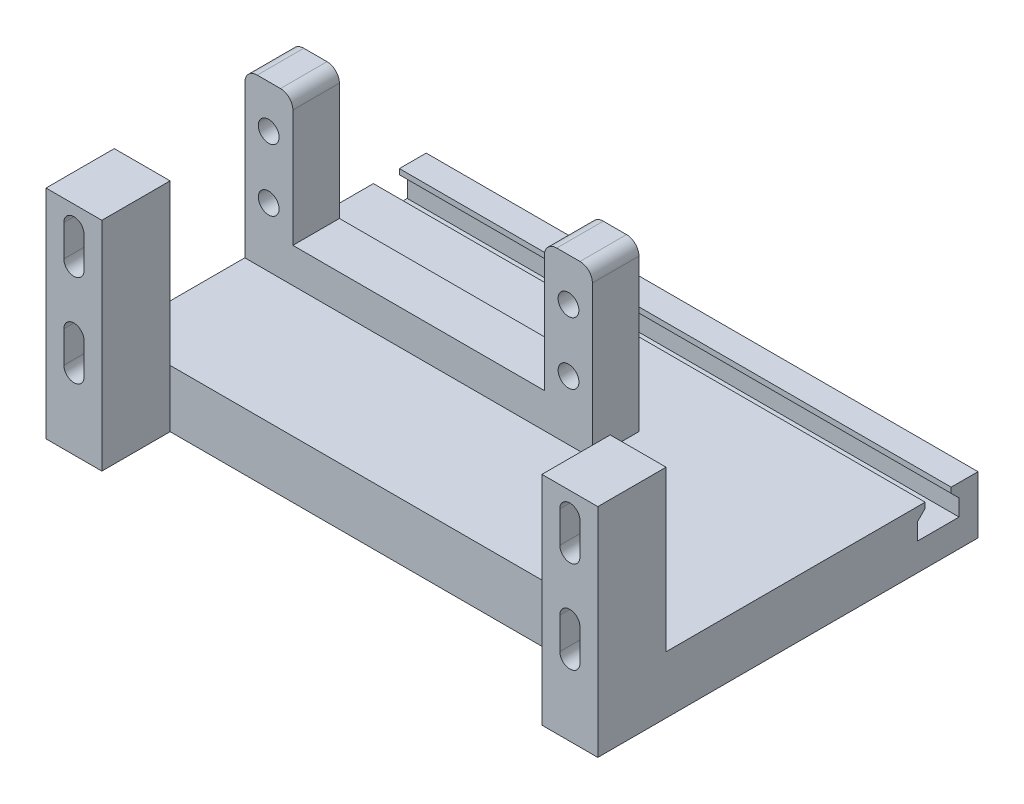
SolidWorks part; units mm, degrees
ref_plane "Front Plane" through (0, 0, 0) normal (0, 0, 1) x (1, 0, 0)
ref_plane "Top Plane" through (0, 0, 0) normal (0, 1, 0) x (1, 0, 0)
ref_plane "Right Plane" through (0, 0, 0) normal (1, 0, 0) x (0, 0, -1)
sketch "Sketch1" plane through (0, 0, 0) normal (0, 1, 0) x (1, 0, 0)
  line L1 (-44.45, -19.625) -> (44.45, -19.625)
  line L2 (-44.45, -19.625) -> (-44.45, 19.625)
  line L3 (-44.45, 19.625) -> (44.45, 19.625)
  line L4 (44.45, -19.625) -> (44.45, 19.625)
  line L5 (-44.45, -19.625) -> (44.45, 19.625) construction
  line L6 (-44.45, 19.625) -> (44.45, -19.625) construction
  point P0 (0, 0)
  dimension "D1" = 88.9
  dimension "D2" = 39.25
extrude "Boss-Extrude1" add sketch "Sketch1" along normal blind 9.25
sketch "Sketch2" plane through (0, 9.25, 0) normal (0, 1, 0) x (1, 0, 0)
  line L0 (0, 19.625) -> (0, -1.985) construction
  line L2 (-44.45, 19.625) -> (-44.45, -19.625) construction
  line L3 (-44.45, -9.5982) -> (11.55, -9.5982)
  line L4 (-44.45, -9.5982) -> (-44.45, -2.0982)
  line L5 (-44.45, -2.0982) -> (11.55, -2.0982)
  line L6 (11.55, -9.5982) -> (11.55, -2.0982)
  line L7 (-44.45, -9.5982) -> (11.55, -2.0982) construction
  line L8 (-44.45, -2.0982) -> (11.55, -9.5982) construction
  line L9 (44.45, 19.625) -> (-44.45, 19.625) construction
  point P9 (-16.45, -5.8482)
  dimension "D1" = 56
  dimension "D2" = 7.5
  dimension "D3" = 21.61
extrude "Boss-Extrude2" add sketch "Sketch2" along normal blind 26.49
sketch "Sketch3" plane through (0, 0, 9.5982) normal (0, 0, 1) x (1, 0, 0)
  line L0 (-16.45, 9.25) -> (-16.45, 14.86) construction
  line L1 (-44.45, 9.25) -> (11.55, 9.25) construction
  line L2 (-36.705, 14.86) -> (3.805, 14.86)
  line L3 (3.805, 14.86) -> (3.805, 35.74)
  line L4 (-44.45, 35.74) -> (11.55, 35.74) construction
  line L5 (3.805, 35.74) -> (-36.705, 35.74)
  line L6 (-36.705, 35.74) -> (-36.705, 14.86)
  point P7 (-16.45, 14.86)
extrude "Cut-Extrude2" cut sketch "Sketch3" against normal blind 8.49
sketch "Sketch5" plane through (0, 0, 9.5982) normal (0, 0, 1) x (1, 0, 0)
  line L0 (-16.45, 9.25) -> (-16.45, 18.82) construction
  line L1 (-44.45, 9.25) -> (11.55, 9.25) construction
  line L2 (-40.6, 18.82) -> (7.7, 18.82) construction
  line L3 (-40.6, 18.82) -> (-40.6, 28.82) construction
  circle A0 centre (-40.6, 18.82) radius 1.675
  circle A1 centre (-40.6, 28.82) radius 1.675
  circle A2 centre (7.7, 18.82) radius 1.675
  circle A3 centre (7.7, 28.82) radius 1.675
  point P7 (-16.45, 18.82)
  dimension "D1" = 3.35
  dimension "D2" = 3.35
extrude "Cut-Extrude3" cut sketch "Sketch5" against normal blind 8.49
sketch "Sketch10" plane through (-44.45, 0, 0) normal (-1, 0, 0) x (0, 0, 1)
  line L0 (-19.625, 9.25) -> (-19.625, 4.4433) construction
  line L1 (-19.625, 9.25) -> (-19.625, 0) construction
  line L2 (-19.625, 4.4433) -> (-16.575, 4.4433) construction
  line L3 (-16.575, 4.4433) -> (-9.845, 4.4433)
  line L4 (-16.575, 4.4433) -> (-16.575, 7.1133)
  line L5 (-9.845, 4.4433) -> (-9.845, 7.1133)
  line L6 (-19.625, 9.25) -> (-15.305, 9.25) construction
  line L7 (-19.625, 9.25) -> (2.0982, 9.25) construction
  line L8 (-15.305, 9.25) -> (-11.115, 9.25)
  line L9 (-11.1178, 8.3861) -> (-11.115, 9.25)
  line L10 (-11.1178, 8.3861) -> (-9.845, 7.1133)
  line L11 (-16.575, 7.1133) -> (-15.3022, 8.3861)
  line L12 (-15.3022, 8.3861) -> (-15.305, 9.25)
extrude "Cut-Extrude4" cut sketch "Sketch10" against normal blind 91.49
fillet "Fillet1" radius 2 2 edges at (-36.705, 35.74, 5.8482) (-44.45, 35.74, 5.8482)
fillet "Fillet2" radius 2 2 edges at (11.55, 35.74, 5.8482) (3.805, 35.74, 5.8482)
sketch "Sketch12" plane through (0, 0, 19.625) normal (0, 0, 1) x (1, 0, 0)
  line L1 (-44.45, 0) -> (44.45, 0)
  line L2 (-44.45, 0) -> (-44.45, 9.25)
  line L3 (-44.45, 9.25) -> (44.45, 9.25)
  line L4 (44.45, 0) -> (44.45, 9.25)
  line L5 (-44.45, 0) -> (44.45, 9.25) construction
  line L6 (-44.45, 9.25) -> (44.45, 0) construction
  point P4 (0, 4.625)
extrude "Boss-Extrude3" add sketch "Sketch12" along normal blind 11
sketch "Sketch16" plane through (0, 0, 0) normal (0, 1, 0) x (1, 0, 0)
  line L1 (44.45, -30.625) -> (35.45, -30.625)
  line L2 (44.45, -30.625) -> (44.45, -41.625)
  line L3 (44.45, -41.625) -> (35.45, -41.625)
  line L4 (35.45, -30.625) -> (35.45, -41.625)
  line L5 (44.45, -30.625) -> (35.45, -41.625) construction
  line L6 (44.45, -41.625) -> (35.45, -30.625) construction
  point P4 (39.95, -36.125)
  dimension "D1" = 11
  dimension "D2" = 9
extrude "Boss-Extrude5" add sketch "Sketch16" along normal blind 35
sketch "Sketch17" plane through (0, 0, 30.625) normal (0, 0, -1) x (-1, 0, 0)
  line L0 (-39.95, 9.25) -> (-39.95, 14.25) construction
  line L1 (-44.45, 9.25) -> (-35.45, 9.25) construction
  line L2 (-39.95, 10.085) -> (-39.95, 18.415) construction
  line L3 (-41.575, 11.71) -> (-38.325, 11.71) construction
  line L4 (-41.575, 11.71) -> (-41.575, 16.79) construction
  line L5 (-41.575, 16.79) -> (-38.325, 16.79) construction
  line L6 (-38.325, 11.71) -> (-38.325, 16.79) construction
  line L7 (-41.575, 11.71) -> (-38.325, 16.79) construction
  line L8 (-41.575, 16.79) -> (-38.325, 11.71) construction
  line L9 (-41.575, 11.71) -> (-41.575, 16.79)
  line L10 (-38.325, 16.79) -> (-38.325, 11.71)
  arc A0 (-41.575, 16.79) -> (-38.325, 16.79) centre (-39.95, 16.79) cw construction
  arc A1 (-38.325, 11.71) -> (-41.575, 11.71) centre (-39.95, 11.71) cw construction
  arc A2 (-41.575, 16.79) -> (-38.325, 16.79) centre (-39.95, 16.79) cw
  arc A3 (-38.325, 11.71) -> (-41.575, 11.71) centre (-39.95, 11.71) cw
  point P11 (-39.95, 14.25)
  dimension "D1" = 5.08
  dimension "D2" = 3.25
extrude "Cut-Extrude5" cut sketch "Sketch17" against normal blind 16
sketch "Sketch19" plane through (0, 0, 30.625) normal (0, 0, -1) x (-1, 0, 0)
  line L0 (-39.95, 22.3505) -> (-39.95, 29.0867) construction
  line L1 (-39.95, 23.1855) -> (-39.95, 34.9879) construction
  line L2 (-41.575, 26.5467) -> (-38.325, 26.5467) construction
  line L3 (-41.575, 26.5467) -> (-41.575, 31.6267) construction
  line L4 (-41.575, 31.6267) -> (-38.325, 31.6267) construction
  line L5 (-38.325, 26.5467) -> (-38.325, 31.6267) construction
  line L6 (-41.575, 26.5467) -> (-38.325, 31.6267) construction
  line L7 (-41.575, 31.6267) -> (-38.325, 26.5467) construction
  line L8 (-41.575, 26.5467) -> (-41.575, 31.6267)
  line L9 (-38.325, 31.6267) -> (-38.325, 26.5467)
  line L10 (-39.95, 35) -> (-39.95, 9.25) construction
  line L11 (-44.45, 35) -> (-35.45, 35) construction
  line L12 (-44.45, 9.25) -> (-35.45, 9.25) construction
  arc A0 (-41.575, 31.6267) -> (-38.325, 31.6267) centre (-39.95, 31.6267) cw construction
  arc A1 (-38.325, 26.5467) -> (-41.575, 26.5467) centre (-39.95, 26.5467) cw construction
  arc A2 (-41.575, 31.6267) -> (-38.325, 31.6267) centre (-39.95, 31.6267) cw
  arc A3 (-38.325, 26.5467) -> (-41.575, 26.5467) centre (-39.95, 26.5467) cw
  point P9 (-39.95, 29.0867)
  dimension "D1" = 5.08
  dimension "D2" = 3.25
extrude "Cut-Extrude6" cut sketch "Sketch19" against normal blind 16
mirror "Mirror1" about plane through (0, 0, 0) normal (1, 0, 0) of "Boss-Extrude5", "Cut-Extrude5", "Cut-Extrude6"
